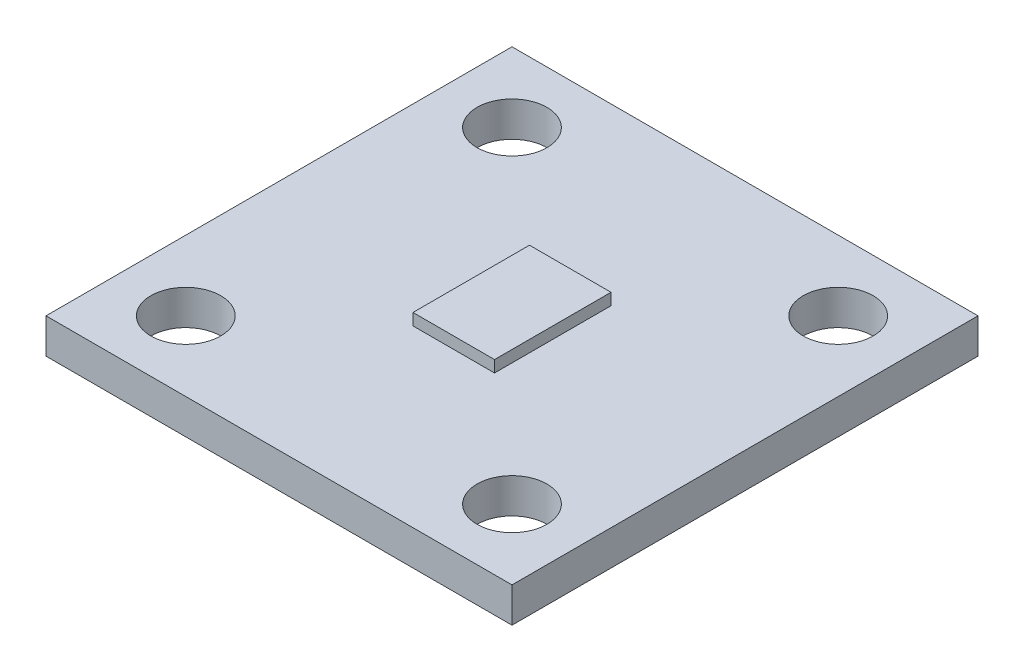
SolidWorks part; units mm, degrees
ref_plane "前视基准面" through (0, 0, 0) normal (0, 0, 1) x (1, 0, 0)
ref_plane "上视基准面" through (0, 0, 0) normal (0, 1, 0) x (1, 0, 0)
ref_plane "右视基准面" through (0, 0, 0) normal (1, 0, 0) x (0, 0, -1)
sketch "草图1" plane through (0, 0, 0) normal (0, 1, 0) x (1, 0, 0)
  line L0 (10, 20) -> (10, 0) construction
  line L1 (0, 0) -> (20, 0)
  line L2 (0, 0) -> (0, 20)
  line L3 (0, 20) -> (20, 20)
  line L4 (20, 0) -> (20, 20)
  line L5 (0, 10) -> (20, 10) construction
  circle A0 centre (3, 17) radius 1.5
  circle A1 centre (17, 17) radius 1.5
  circle A2 centre (17, 3) radius 1.5
  circle A3 centre (3, 3) radius 1.5
  point P11 (0, 0)
  dimension "D3" = 3
  dimension "D1" = 20
  dimension "D2" = 20
  dimension "D4" = 3
  dimension "D5" = 3
extrude "凸台-拉伸1" add sketch "草图1" along normal blind 1.5
sketch "草图2" plane through (0, 1.5, 0) normal (0, 1, 0) x (1, 0, 0)
  line L0 (0, 20) -> (20, 0) construction
  line L1 (8.25, 12.5) -> (11.75, 12.5)
  line L2 (8.25, 12.5) -> (8.25, 7.5)
  line L3 (8.25, 7.5) -> (11.75, 7.5)
  line L4 (11.75, 12.5) -> (11.75, 7.5)
  line L5 (8.25, 7.5) -> (11.75, 12.5) construction
  point P8 (10, 10)
  point P9 (10, 10)
  dimension "D1" = 5
  dimension "D2" = 3.5
extrude "凸台-拉伸2" add sketch "草图2" along normal blind 0.5
